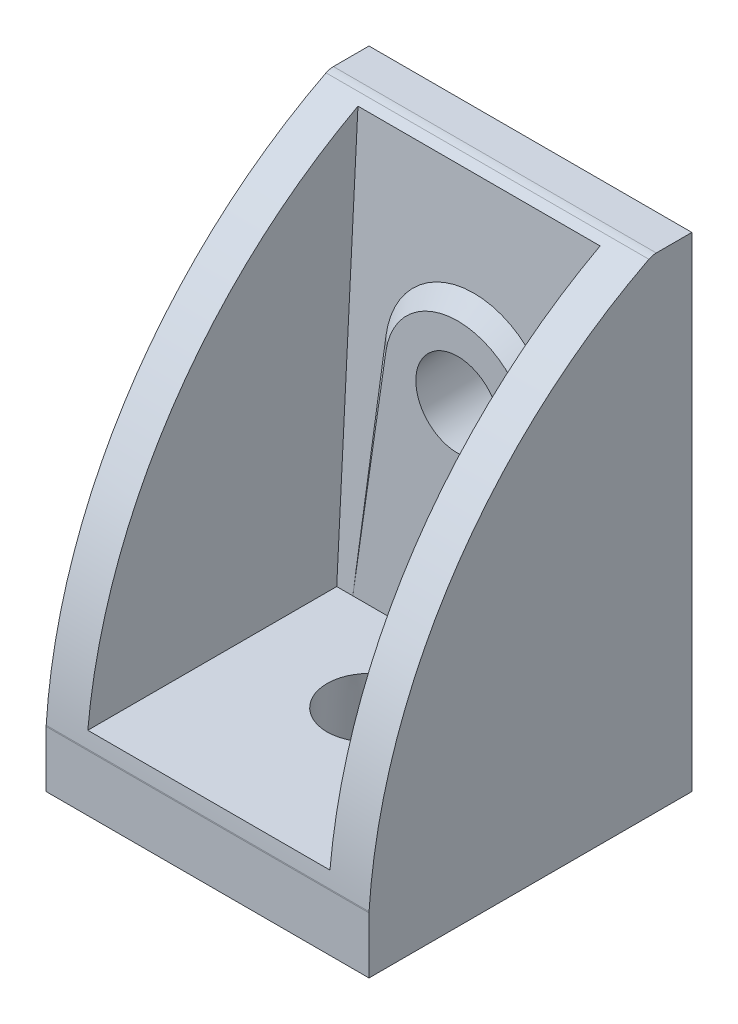
SolidWorks part; units mm, degrees
ref_plane "Front Plane" through (0, 0, 0) normal (0, 0, 1) x (1, 0, 0)
ref_plane "Top Plane" through (0, 0, 0) normal (0, 1, 0) x (1, 0, 0)
ref_plane "Right Plane" through (0, 0, 0) normal (1, 0, 0) x (0, 0, -1)
ref_plane "Plane1" through (0, 0, 0) normal (1, 0, 0) x (0, 0, -1)
sketch "Sketch1" plane through (0, 0, 0) normal (1, 0, 0) x (0, 0, -1)
  line L0 (-20, 3.4921) -> (-20, 0)
  line L1 (-20, 0) -> (0, 0)
  line L2 (0, 0) -> (0, 30)
  line L3 (0, 30) -> (-2.2048, 30)
  arc A0 (-2.2048, 30) -> (-2.6607, 29.89) centre (-2.2048, 29) ccw
  arc A1 (-2.6607, 29.89) -> (-19.9977, 3.5593) centre (11.93, 1.41) ccw
  arc A2 (-19.9977, 3.5593) -> (-20, 3.4921) centre (-19, 3.4921) ccw
extrude "Boss-Extrude1" add sketch "Sketch1" along normal blind 20
ref_plane "Plane2" through (10, 0, 0) normal (1, 0, 0) x (0, 0, -1)
sketch "Sketch2" plane through (10, 0, 0) normal (1, 0, 0) x (0, 0, -1)
  line L0 (-20, 30) -> (-20, 4.5)
  line L1 (-20, 4.5) -> (-4.5, 4.5)
  line L2 (-4.5, 4.5) -> (-3.1636, 30)
  line L3 (-3.1636, 30) -> (-20, 30)
extrude "Cut-Extrude1" cut sketch "Sketch2" against normal blind 7.5 and the other way blind 7.5
ref_plane "Plane3" through (10, 0, 0) normal (1, 0, 0) x (0, 0, -1)
sketch "Sketch3" plane through (10, 0, 0) normal (1, 0, 0) x (0, 0, -1)
  line L0 (-0.5, 26.5) -> (-0.5, 23.5)
  line L1 (-0.5, 23.5) -> (1, 24.366)
  line L2 (1, 24.366) -> (1, 25.634)
  line L3 (1, 25.634) -> (-0.5, 26.5)
extrude "Boss-Extrude2" add sketch "Sketch3" against normal blind 3 and the other way blind 3
ref_plane "Plane4" through (10, 0, 0) normal (1, 0, 0) x (0, 0, -1)
sketch "Sketch4" plane through (10, 0, 0) normal (1, 0, 0) x (0, 0, -1)
  line L0 (-0.5, 13) -> (-0.5, 4)
  line L1 (-0.5, 4) -> (1, 4.866)
  line L2 (1, 4.866) -> (1, 12.134)
  line L3 (1, 12.134) -> (-0.5, 13)
extrude "Boss-Extrude3" add sketch "Sketch4" against normal blind 3 and the other way blind 3
ref_plane "Plane5" through (0, 0, 4.5) normal (0, 0, 1) x (1, 0, 0)
sketch "Sketch5" plane through (0, 0, 4.5) normal (0, 0, 1) x (1, 0, 0)
  line L0 (3.4955, 4.5) -> (16.5045, 4.5)
  line L1 (16.5045, 4.5) -> (14.4534, 18.6457)
  line L2 (5.5466, 18.6457) -> (3.4955, 4.5)
  arc A0 (14.4534, 18.6457) -> (5.5466, 18.6457) centre (10, 18) ccw
extrude "Boss-Extrude4" add sketch "Sketch5" against normal blind 2 draft 45 draft outward yes
ref_plane "Plane6" through (0, 0.5, 0) normal (0, 1, 0) x (1, 0, 0)
sketch "Sketch6" plane through (0, 0.5, 0) normal (0, 1, 0) x (1, 0, 0)
  line L0 (7.075, -12.925) -> (12.925, -12.925)
  line L1 (12.925, -12.925) -> (12.925, -7.075)
  line L2 (12.925, -7.075) -> (7.075, -7.075)
  line L3 (7.075, -7.075) -> (7.075, -12.925)
extrude "Boss-Extrude5" add sketch "Sketch6" against normal blind 1.5 draft 6
ref_plane "Plane7" through (0, 0, 0) normal (0, 1, 0) x (1, 0, 0)
sketch "Sketch7" plane through (0, 0, 0) normal (0, 1, 0) x (1, 0, 0)
  line L0 (7.075, -10.835) -> (9.165, -10.835)
  line L1 (9.165, -10.835) -> (9.165, -12.925)
  line L2 (9.165, -12.925) -> (10.835, -12.925)
  line L3 (10.835, -12.925) -> (10.835, -10.835)
  line L4 (10.835, -10.835) -> (12.925, -10.835)
  line L5 (12.925, -10.835) -> (12.925, -9.165)
  line L6 (12.925, -9.165) -> (10.835, -9.165)
  line L7 (10.835, -9.165) -> (10.835, -7.075)
  line L8 (10.835, -7.075) -> (9.165, -7.075)
  line L9 (9.165, -7.075) -> (9.165, -9.165)
  line L10 (9.165, -9.165) -> (7.075, -9.165)
  line L11 (7.075, -9.165) -> (7.075, -10.835)
extrude "Cut-Extrude2" cut sketch "Sketch7" against normal blind 1 draft 6 draft outward yes
ref_plane "Plane8" through (10, 0, 0) normal (1, 0, 0) x (0, 0, -1)
sketch "Sketch8" plane through (10, 0, 0) normal (1, 0, 0) x (0, 0, -1)
  line L0 (-4.5, 18) -> (-4.5, 20.6)
  line L1 (-4.5, 20.6) -> (0, 20.8358)
  line L2 (0, 20.8358) -> (0, 18)
  line L3 (0, 18) -> (-4.5, 18)
  line L4 (0, 18) -> (-4.5, 18) construction
revolve "Cut-Revolve1" cut sketch "Sketch8" angle 360 about L4
ref_plane "Plane9" through (10, 0, 0) normal (1, 0, 0) x (0, 0, -1)
sketch "Sketch9" plane through (10, 0, 0) normal (1, 0, 0) x (0, 0, -1)
  line L0 (-10, 4.5) -> (-7.4, 4.5)
  line L1 (-7.4, 4.5) -> (-7.1118, -1)
  line L2 (-7.1118, -1) -> (-10, -1)
  line L3 (-10, -1) -> (-10, 4.5)
  line L4 (-10, -1) -> (-10, 4.5) construction
revolve "Cut-Revolve2" cut sketch "Sketch9" angle 360 about L4
